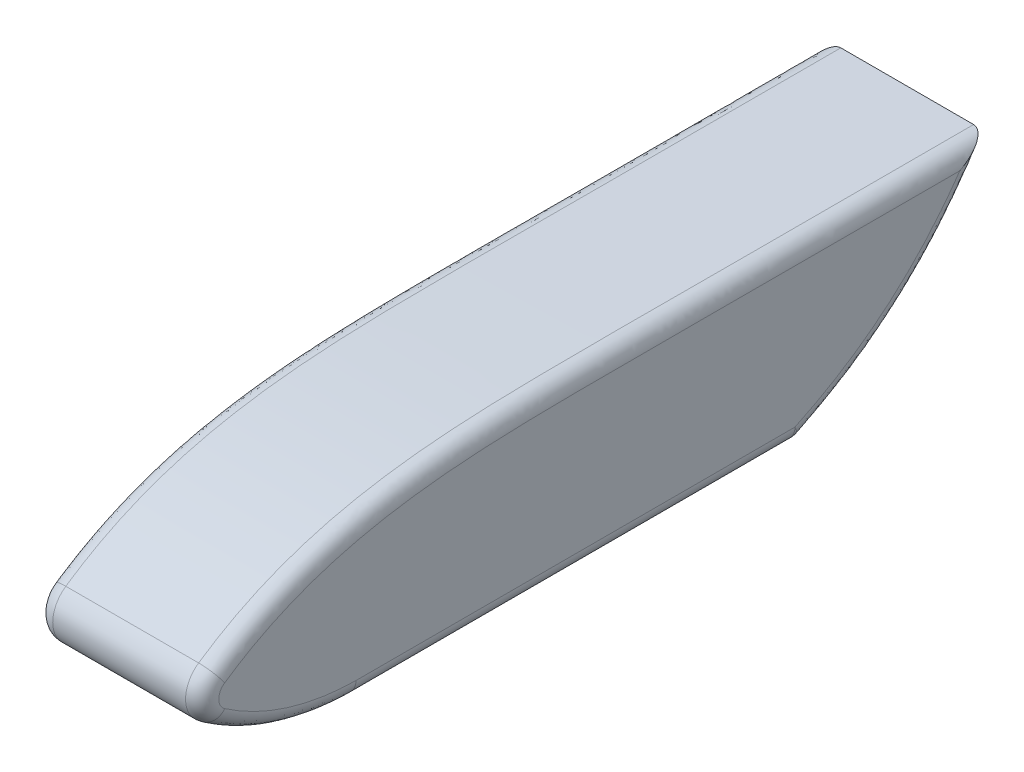
SolidWorks part; units mm, degrees
ref_plane "Front Plane" through (0, 0, 0) normal (0, 0, 1) x (1, 0, 0)
ref_plane "Top Plane" through (0, 0, 0) normal (0, 1, 0) x (1, 0, 0)
ref_plane "Right Plane" through (0, 0, 0) normal (1, 0, 0) x (0, 0, -1)
sketch "Sketch1" plane through (0, 0, 0) normal (0, 0, 1) x (1, 0, 0)
  line L1 (-69.8953, 71.8586) -> (80.1047, 71.8586)
  line L2 (-69.8953, 71.8586) -> (-69.8953, -53.1414)
  line L3 (-69.8953, -53.1414) -> (80.1047, -53.1414)
  line L4 (80.1047, 71.8586) -> (80.1047, -53.1414)
  dimension "D1" = 150
  dimension "D2" = 125
extrude "Boss-Extrude1" add sketch "Sketch1" along normal blind 400
sketch "Sketch2" plane through (80.1047, 0, 0) normal (1, 0, 0) x (0, 0, -1)
  line L0 (-400, -53.1414) -> (0, -53.1414)
  line L1 (-400, 71.8586) -> (0, 71.8586) construction
  line L2 (-199.6293, 71.8586) -> (-199.6293, 102.8586) construction
  line L3 (0.1253, 91.8586) -> (264, 91.8586) construction
  line L4 (264, 91.8586) -> (264, 71.8586) construction
  line L5 (264, 71.8586) -> (0, 71.8586) construction
  line L7 (416.4, -13.1414) -> (111.6, -13.1414) construction
  line L8 (416.4, -13.1414) -> (416.4, -43.1414) construction
  line L9 (416.4, -43.1414) -> (111.6, -43.1414) construction
  line L10 (111.6, -13.1414) -> (111.6, -43.1414) construction
  line L11 (281.6, 26.8586) -> (246.4, 26.8586) construction
  line L12 (281.6, 26.8586) -> (281.6, -43.1414) construction
  line L13 (281.6, -43.1414) -> (246.4, -43.1414) construction
  line L14 (246.4, 26.8586) -> (246.4, -43.1414) construction
  line L15 (275.6008, 71.8586) -> (252.3992, 71.8586) construction
  line L16 (275.6008, 71.8586) -> (275.6008, 26.8586) construction
  line L17 (275.6008, 26.8586) -> (252.3992, 26.8586) construction
  line L18 (252.3992, 71.8586) -> (252.3992, 26.8586) construction
  arc A0 (-527.0831, 31.6863) -> (-527.0831, -13.1414) centre (-511.6964, 9.2725) ccw
  spline S0 degree 3 poles (-527.0831, 31.6863) (-502.1305, 48.8156) (-400.7917, 99.0301) (-226.1773, 103.791) (-20.0307, 102.5362) (104.7761, 103.005) (173.0631, 102.8586) knots 0 0 0 0 0.12454 0.476334 0.711394 1 1 1 1
  spline S1 degree 3 poles (-400, -53.1414) (-445.3535, -52.4976) (-488.6296, -39.5389) (-527.0831, -13.1414) knots 0 0 0 0 1 1 1 1
  spline S2 degree 2 poles (0, -53.1414) (109.6578, -2.766) (173.0631, 102.8586) knots 0 0 0 1 1 1
  point P16 (264, 91.8586)
  point P17 (-200, 71.8586)
  point P26 (264, -43.1414)
  point P27 (264, -13.1414)
  point P28 (264, -43.1414)
  point P41 (264, 71.8586)
  dimension "D1" = 464
  dimension "D2" = 31
  dimension "D3" = 20
  dimension "D4" = 304.8
  dimension "D5" = 30
  dimension "D6" = 70
  dimension "D7" = 35.2
  dimension "D8" = 45
extrude "Boss-Extrude2" add sketch "Sketch2" against normal up to surface (150 mm away) up to face at (-69.8953, 9.3586, 200)
fillet "Fillet1" radius 15 11 edges at (-69.8953, 9.2725, 538.8833) (80.1047, 9.2725, 538.8833) (80.1047, -53.1414, 200) (-69.8953, -53.1414, 200) (5.1047, -53.1414, 0)
